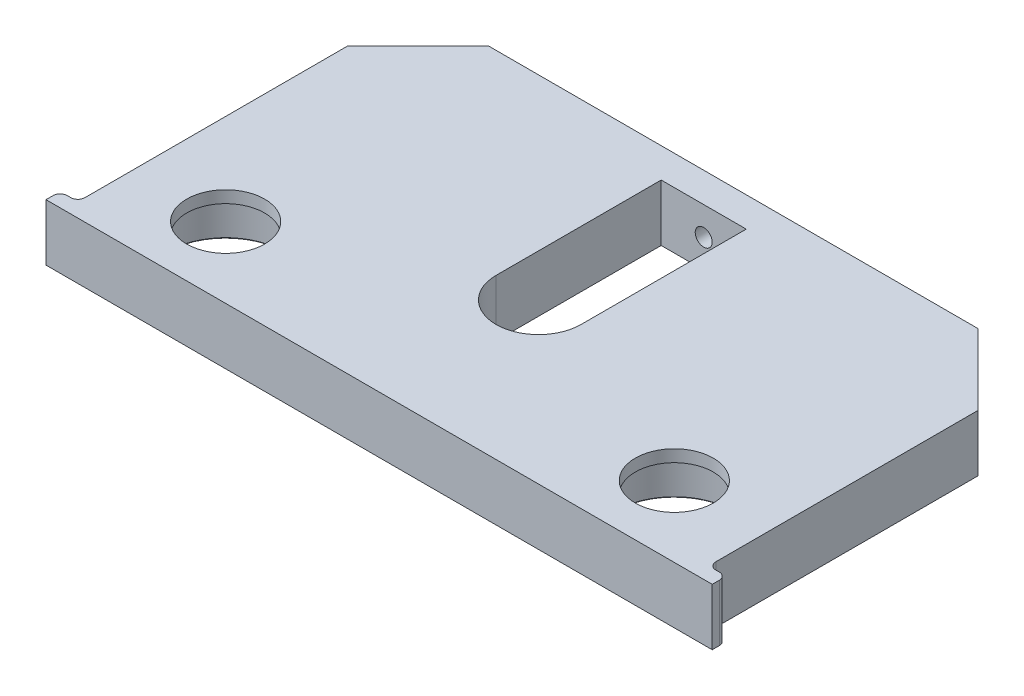
SolidWorks part; units mm, degrees
ref_plane "Front Plane" through (0, 0, 0) normal (0, 0, 1) x (1, 0, 0)
ref_plane "Top Plane" through (0, 0, 0) normal (0, 1, 0) x (1, 0, 0)
ref_plane "Right Plane" through (0, 0, 0) normal (1, 0, 0) x (0, 0, -1)
sketch "Sketch1" plane through (0, 0, 0) normal (0, 1, 0) x (1, 0, 0)
  line L0 (-445, 0) -> (445, 0)
  line L1 (445, 20) -> (445, 400)
  line L2 (345, 500) -> (-345, 500)
  line L3 (-445, 400) -> (-445, 20)
  line L4 (-345, 500) -> (-445, 400)
  line L5 (445, 400) -> (345, 500)
  line L6 (0, 0) -> (0, 539.6941) construction
  line L7 (445, 20) -> (470, 20)
  line L8 (470, 20) -> (470, 0)
  line L9 (470, 0) -> (445, 0)
  line L10 (-470, 0) -> (-445, 0)
  line L11 (-470, 20) -> (-470, 0)
  line L12 (-445, 20) -> (-470, 20)
  line L13 (-60, 458) -> (60, 458)
  line L14 (-316.5, 225) -> (316.5, 225) construction
  line L15 (-316.5, 231) -> (316.5, 231) construction
  line L16 (-60, 225) -> (-60, 458)
  line L17 (60, 225) -> (60, 458)
  circle A0 centre (-316.5, 100) radius 55
  circle A1 centre (-316.5, 100) radius 125 construction
  circle A2 centre (316.5, 100) radius 55
  circle A3 centre (316.5, 100) radius 125 construction
  arc A4 (-59.6992, 231) -> (59.6992, 231) centre (0, 225) ccw
  point P3 (445, 500)
  point P4 (0, 0)
  point P5 (-445, 500)
  point P27 (0, 458)
  point P33 (0, 0)
  dimension "D3" = 250
  dimension "D4" = 110
  dimension "D12" = 120
  dimension "D1" = 890
  dimension "D2" = 500
  dimension "D7" = 633
  dimension "D8" = 20
  dimension "D9" = 470
  dimension "D10" = 100
  dimension "D13" = 42
  dimension "D14" = 233
  dimension "D11" = 6
extrude "Boss-Extrude1" add sketch "Sketch1" along normal mid plane 80 contours L3 L12 L11 L10 L0 L9 L8 L7 L1 L5 L2 L4 A4 L16 L13 L17 A0 A2
fillet "Fillet1" radius 10 4 edges at (-470, 0, -20) (-445, 0, -20) (470, 0, -20) (445, 0, -20)
sketch "Sketch2" plane through (0, 0, -458) normal (0, 0, 1) x (1, 0, 0)
  circle A0 centre (0, 0) radius 12
  dimension "D1" = 24
extrude "Cut-Extrude1" cut sketch "Sketch2" against normal blind 80
sketch "Sketch3" plane through (0, -40, 0) normal (0, -1, 0) x (1, 0, 0)
  circle A0 centre (-316.5, -100) radius 82.5
  circle A1 centre (316.5, -100) radius 82.5
  dimension "D1" = 165
extrude "Cut-Extrude2" cut sketch "Sketch3" against normal blind 63
chamfer "Chamfer1" distance 2 angle 45 4 edges at (-316.5, -40, -182.5) (-316.5, 23, -182.5) (316.5, -40, -182.5) (316.5, 23, -182.5)
